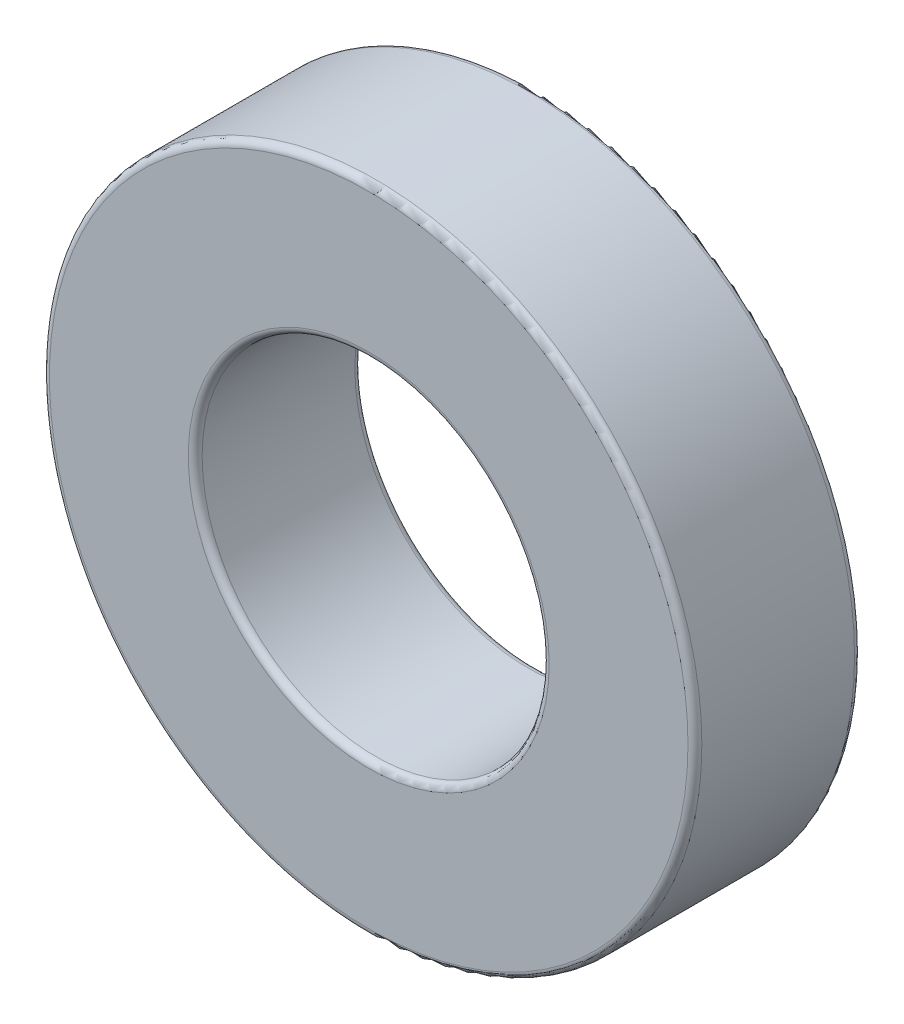
SolidWorks part; units mm, degrees
material "Alloy Steel"
ref_plane "Front Plane" through (0, 0, 0) normal (0, 0, 1) x (1, 0, 0)
ref_plane "Top Plane" through (0, 0, 0) normal (0, 1, 0) x (1, 0, 0)
ref_plane "Right Plane" through (0, 0, 0) normal (1, 0, 0) x (0, 0, -1)
sketch "Sketch1" plane through (0, 0, 0) normal (0, 0, 1) x (1, 0, 0)
  circle A0 centre (0, 0) radius 23.5
  circle A1 centre (0, 0) radius 12.5
  dimension "D1" = 47
  dimension "D2" = 25
extrude "Boss-Extrude1" add sketch "Sketch1" along normal blind 12
fillet "Fillet1" radius 0.5 4 edges at (23.5, 0, 0) (23.5, 0, 12) (12.5, 0, 0) (12.5, 0, 12)
